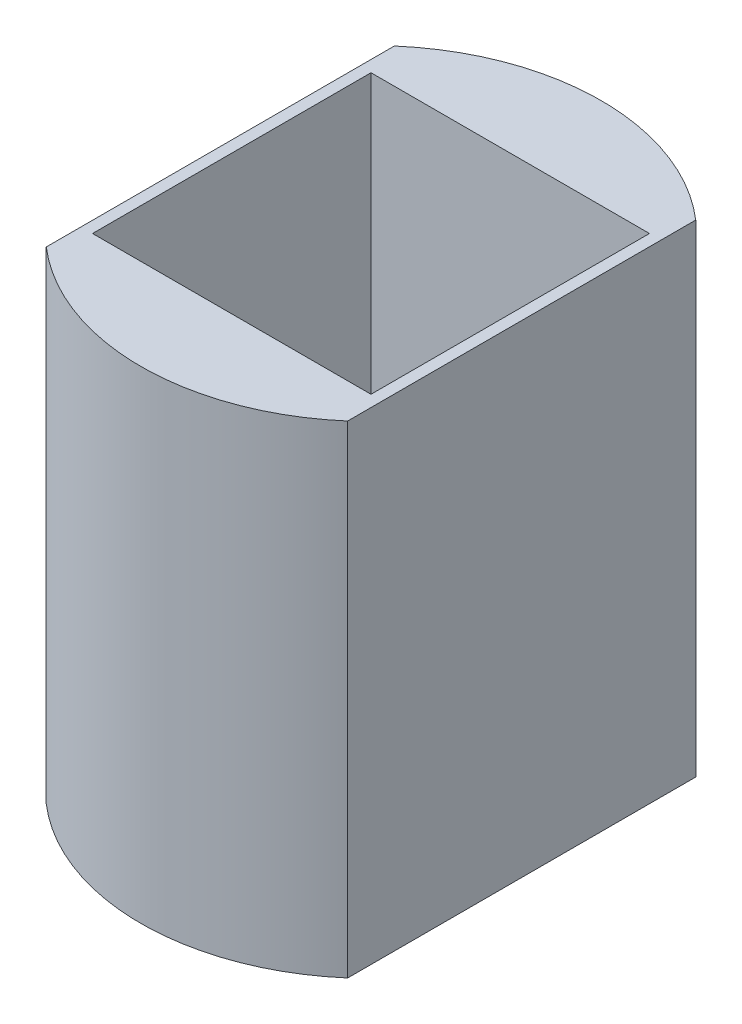
SolidWorks part; units mm, degrees
ref_plane "Front Plane" through (0, 0, 0) normal (0, 0, 1) x (1, 0, 0)
ref_plane "Top Plane" through (0, 0, 0) normal (0, 1, 0) x (1, 0, 0)
ref_plane "Right Plane" through (0, 0, 0) normal (1, 0, 0) x (0, 0, -1)
sketch "Sketch1" plane through (0, 0, 0) normal (0, 1, 0) x (1, 0, 0)
  line L1 (-3.4368, -3.9688) -> (3.4368, -3.9688)
  line L2 (-3.4368, -3.9688) -> (-3.4368, 3.9688)
  line L3 (-3.4368, 3.9688) -> (3.4368, 3.9688)
  line L4 (3.4368, -3.9688) -> (3.4368, 3.9688)
  line L5 (-3.4368, -3.9688) -> (3.4368, 3.9688) construction
  line L6 (-3.4368, 3.9688) -> (3.4368, -3.9688) construction
  circle A0 centre (0, 0) radius 5.25
  dimension "D1" = 10.5
  dimension "D2" = 7.9375
extrude "Boss-Extrude1" add sketch "Sketch1" along normal blind 1 contours L1 L4 L3 L2 | L3 A0 | L1 A0
sketch "Sketch2" plane through (0, 1, 0) normal (0, 1, 0) x (1, 0, 0)
  line L1 (-3.175, -3.175) -> (3.175, -3.175)
  line L2 (-3.175, -3.175) -> (-3.175, 3.175)
  line L3 (-3.175, 3.175) -> (3.175, 3.175)
  line L4 (3.175, -3.175) -> (3.175, 3.175)
  line L5 (-3.175, -3.175) -> (3.175, 3.175) construction
  line L6 (-3.175, 3.175) -> (3.175, -3.175) construction
  line L8 (-3.4368, 3.9688) -> (-3.4368, -3.9688)
  line L9 (3.4368, -3.9688) -> (3.4368, 3.9688)
  line L10 (-3.4368, 3.9688) -> (-3.4368, -3.9688)
  line L11 (3.4368, -3.9688) -> (3.4368, 3.9688)
  arc A2 (-3.4368, -3.9688) -> (3.4368, -3.9688) centre (0, 0) ccw
  arc A3 (3.4368, 3.9688) -> (-3.4368, 3.9688) centre (0, 0) ccw
  arc A4 (-3.4368, -3.9688) -> (3.4368, -3.9688) centre (0, 0) ccw
  arc A5 (3.4368, 3.9688) -> (-3.4368, 3.9688) centre (0, 0) ccw
  point P0 (0, 0)
  line M5 (-3.4368, 3.9688) -> (-3.4368, -3.9688)
  arc M6 (-3.4368, -3.9688) -> (3.4368, -3.9688) centre (0, 0) ccw
  line M7 (3.4368, -3.9688) -> (3.4368, 3.9688)
  arc M8 (3.4368, 3.9688) -> (-3.4368, 3.9688) centre (0, 0) ccw
  dimension "D1" = 6.35
  dimension "D2" = 0
extrude "Boss-Extrude2" add sketch "Sketch2" along normal blind 10 contours L4 L1 L2 L3 M8 M5 M6 M7 | L10 A4 L11 A5
